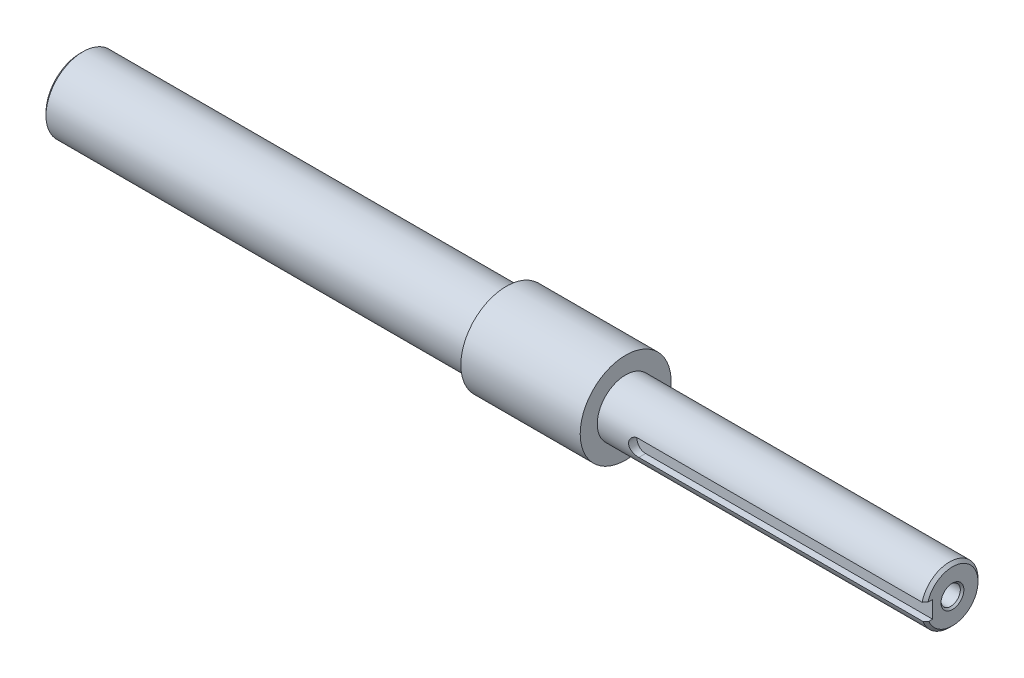
SolidWorks part; units mm, degrees
ref_plane "Front Plane" through (0, 0, 0) normal (0, 0, 1) x (1, 0, 0)
ref_plane "Top Plane" through (0, 0, 0) normal (0, 1, 0) x (1, 0, 0)
ref_plane "Right Plane" through (0, 0, 0) normal (1, 0, 0) x (0, 0, -1)
sketch "Sketch1" plane through (0, 0, 0) normal (0, 0, 1) x (1, 0, 0)
  line L0 (0, 0) -> (307, 0) construction
  line L1 (0, 0) -> (0, 13)
  line L2 (0, 13) -> (150, 13)
  line L3 (150, 13) -> (150, 16)
  line L4 (150, 16) -> (192, 16)
  line L5 (192, 16) -> (192, 10)
  line L6 (192, 10) -> (307, 10)
  line L7 (307, 10) -> (307, 0)
  line L8 (0, 0) -> (307, 0)
  point P4 (192, 38.9601)
  dimension "D1" = 307
  dimension "D2" = 13
  dimension "D3" = 150
  dimension "D4" = 42
  dimension "D5" = 10
  dimension "D6" = 16
revolve "Revolve1" add sketch "Sketch1" angle 360 about L0
sketch "Sketch2" plane through (0, 0, 0) normal (-1, 0, 0) x (0, 0, 1)
  line L0 (0, 16.3292) -> (0, -16.3292) construction
  point P4 (0, 0)
hole_wizard "Ø5.0mm Dowel Hole1" positions "Sketch3" profile "Sketch4" hole size "Ø5.0" standard "ISO"
sketch "Sketch3" plane through (0, 0, 0) normal (-1, 0, 0) x (0, 0, 1)
  line L0 (0, 16.3292) -> (0, -16.3292) construction
  point P0 (0, 8)
  point P4 (0, -8)
  dimension "D1" = 8
  dimension "D2" = 16
sketch "Sketch4" plane through (0, 8, 0) normal (0, 1, 0) x (0, 0, 1)
  line L0 (0, 0) -> (0, 16.5022)
  line L1 (0, 16.5022) -> (2.5, 15)
  line L2 (2.5, 15) -> (2.5, 0.025)
  line L3 (2.5, 0.025) -> (2.525, 0)
  line L5 (2.525, 0) -> (0, 0)
  line L6 (-2.5, 0.025) -> (-2.525, 0) construction
  line L10 (0, 16.5022) -> (-2.5, 15) construction
  line L11 (0, -6.35) -> (0, 107.95) construction
  dimension "Hole Dia." = 5
  dimension "Hole Depth" = 15
  dimension "Near C'Sink Dia." = 5.05
  dimension "Near C'Sink Angle" = 90
  dimension "Drill Angle" = 118
hole_wizard "M5 Tapped Hole1" positions "Sketch5" profile "Sketch6" tap size "M5" standard "ISO"
sketch "Sketch5" plane through (0, 0, 0) normal (-1, 0, 0) x (0, 0, 1)
  point P0 (0, 0)
sketch "Sketch6" plane through (0, 0, 0) normal (0, 1, 0) x (0, 0, 1)
  line L0 (0, 0) -> (0, 16.2618)
  line L1 (0, 16.2618) -> (2.1, 15)
  line L2 (2.1, 15) -> (2.1, 0.425)
  line L3 (2.1, 0.425) -> (2.525, 0)
  line L5 (2.525, 0) -> (0, 0)
  line L6 (-2.1, 0.425) -> (-2.525, 0) construction
  line L10 (0, 16.2618) -> (-2.1, 15) construction
  line L11 (0, -6.35) -> (0, 107.95) construction
  dimension "Tap Drill Dia." = 4.2
  dimension "Tap Drill Depth" = 15
  dimension "Near C'Sink Dia." = 5.05
  dimension "Near C'Sink Angle" = 90
  dimension "Drill Angle" = 118
cosmetic thread "Hole Thread1" parameters "D1"=10, "D2"=5
ref_plane "Plane1" through (0, 0, 10) normal (0, 0, 1) x (1, 0, 0)
sketch "Sketch7" plane through (0, 0, 10) normal (0, 0, 1) x (1, 0, 0)
  line L0 (307, -10) -> (307, 10) construction
  line L1 (307, 2.5281) -> (206, 2.5281)
  line L2 (307, 2.5281) -> (307, -3.4719)
  line L3 (307, -3.4719) -> (206, -3.4719)
  line L5 (307, 10) -> (192, 10) construction
  arc A0 (206, 2.5281) -> (206, -3.4719) centre (206, -0.4719) ccw
  dimension "D3" = 3
  dimension "D1" = 101
  dimension "D2" = 6
  dimension "D4" = 206
  dimension "D5" = 7.4719
extrude "Cut-Extrude1" cut sketch "Sketch7" against normal blind 3
chamfer "Chamfer1" distance 1 angle 45 2 edges at (0, 0, 13) (307, 0.4947, -9.9878)
hole_wizard "M8 Tapped Hole1" positions "Sketch10" profile "Sketch11" tap size "M8" standard "ISO"
sketch "Sketch10" plane through (307, 0, 0) normal (1, 0, 0) x (0, 0, -1)
  line L0 (0, 16.3292) -> (0, -16.3292) construction
  point P0 (0, 0)
sketch "Sketch11" plane through (307, 0, 0) normal (0, 1, 0) x (0, 0, -1)
  line L0 (0, 0) -> (0, 18.0429)
  line L1 (0, 18.0429) -> (3.4, 16)
  line L2 (3.4, 16) -> (3.4, 0.625)
  line L3 (3.4, 0.625) -> (4.025, 0)
  line L5 (4.025, 0) -> (0, 0)
  line L6 (-3.4, 0.625) -> (-4.025, 0) construction
  line L10 (0, 18.0429) -> (-3.4, 16) construction
  line L11 (0, -6.35) -> (0, 107.95) construction
  dimension "Tap Drill Dia." = 6.8
  dimension "Tap Drill Depth" = 16
  dimension "Near C'Sink Dia." = 8.05
  dimension "Near C'Sink Angle" = 90
  dimension "Drill Angle" = 118
cosmetic thread "Hole Thread2" parameters "D1"=16, "D2"=8
